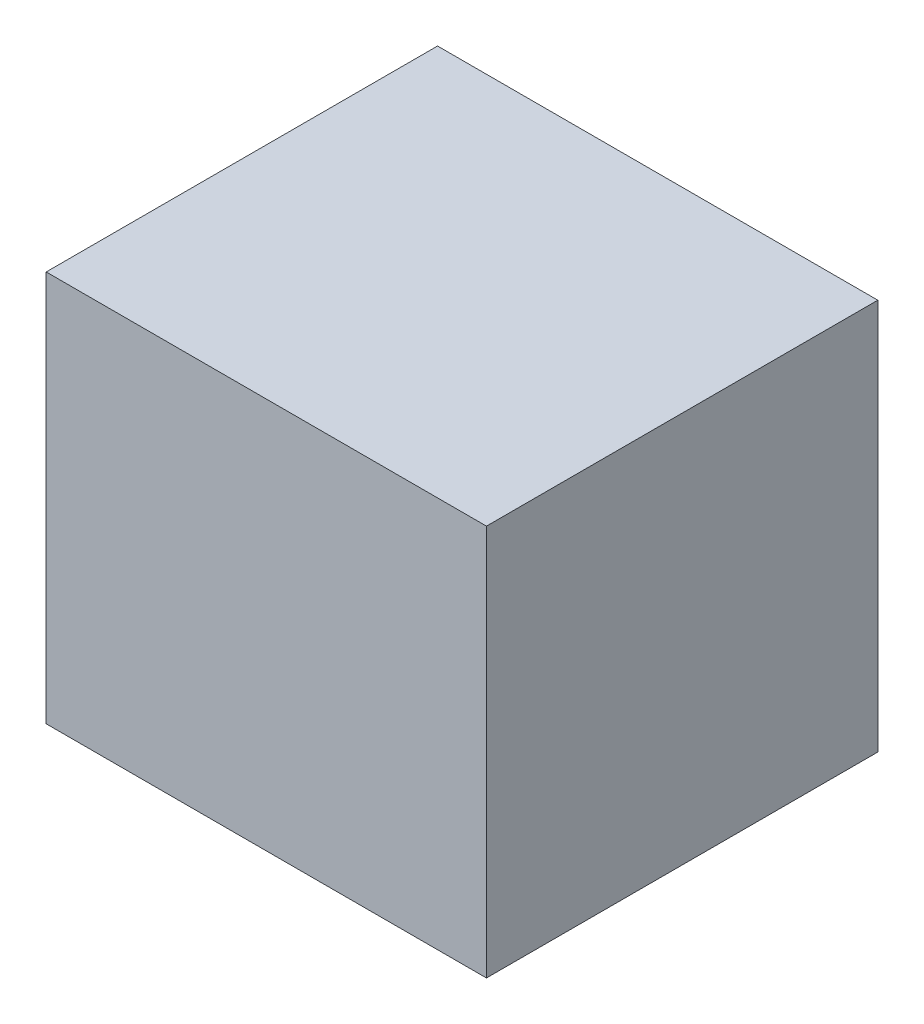
SolidWorks part; units mm, degrees
ref_plane "Plane1" through (0, 0, 0) normal (0, 0, 1) x (1, 0, 0)
ref_plane "Plane2" through (0, 0, 0) normal (0, 1, 0) x (1, 0, 0)
ref_plane "Plane3" through (0, 0, 0) normal (1, 0, 0) x (0, 0, -1)
sketch "Sketch1" plane through (0, 0, 0) normal (0, 0, 1) x (1, 0, 0)
  line L1 (0, 0) -> (57.15, 0)
  line L2 (0, 0) -> (0, 50.8)
  line L3 (0, 50.8) -> (57.15, 50.8)
  line L4 (57.15, 0) -> (57.15, 50.8)
  dimension "D1" = 50.8
  dimension "D2" = 57.15
extrude "Base-Extrude" add sketch "Sketch1" along normal blind 50.8
